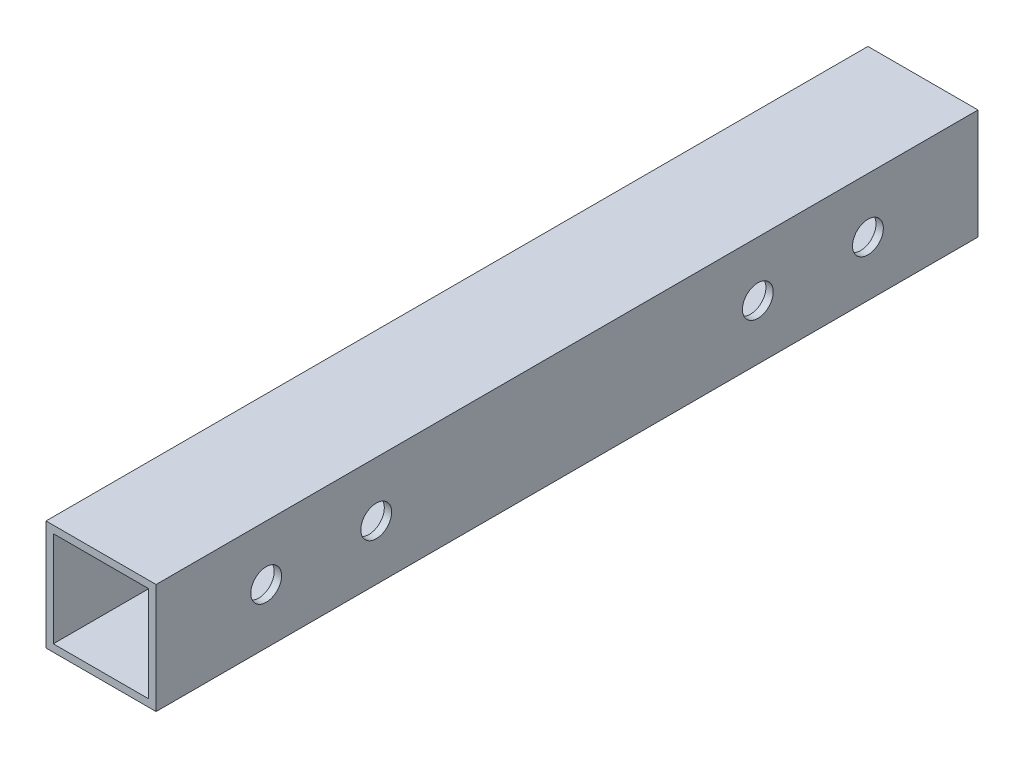
SolidWorks part; units mm, degrees
ref_plane "前视基准面" through (0, 0, 0) normal (0, 0, 1) x (1, 0, 0)
ref_plane "上视基准面" through (0, 0, 0) normal (0, 1, 0) x (1, 0, 0)
ref_plane "右视基准面" through (0, 0, 0) normal (1, 0, 0) x (0, 0, -1)
other "Configuration Table"
sketch "草图1" plane through (0, 0, 0) normal (0, 0, 1) x (1, 0, 0)
  line L1 (-7.5, 7.5) -> (7.5, 7.5)
  line L2 (-7.5, 7.5) -> (-7.5, -7.5)
  line L3 (-7.5, -7.5) -> (7.5, -7.5)
  line L4 (7.5, 7.5) -> (7.5, -7.5)
  line L5 (-7.5, 7.5) -> (7.5, -7.5) construction
  line L6 (-7.5, -7.5) -> (7.5, 7.5) construction
  line L7 (-6.5, 6.5) -> (6.5, 6.5)
  line L8 (-6.5, 6.5) -> (-6.5, -6.5)
  line L9 (-6.5, -6.5) -> (6.5, -6.5)
  line L10 (6.5, 6.5) -> (6.5, -6.5)
  line L11 (-6.5, 6.5) -> (6.5, -6.5) construction
  line L12 (-6.5, -6.5) -> (6.5, 6.5) construction
  point P0 (0, 0)
  point P5 (0, 0)
  dimension "D1" = 15
  dimension "D2" = 15
  dimension "D3" = 1
extrude "凸台-拉伸1" add sketch "草图1" along normal blind 112
sketch "草图3" plane through (7.5, 0, 0) normal (1, 0, 0) x (0, 0, -1)
  line L0 (-112, 0) -> (0, 0) construction
  line L1 (-112, -7.5) -> (-112, 7.5) construction
  line L2 (0, -7.5) -> (0, 7.5) construction
  line L3 (-56, 7.5) -> (-56, -7.5) construction
  line L4 (-112, 7.5) -> (0, 7.5) construction
  line L5 (-112, -7.5) -> (0, -7.5) construction
  circle A0 centre (-15, 0) radius 2.1
  circle A1 centre (-30, 0) radius 2.1
  circle A2 centre (-97, 0) radius 2.1
  circle A3 centre (-82, 0) radius 2.1
  dimension "D1" = 15
  dimension "D3" = 4.2
  dimension "D2" = 15
extrude "切除-拉伸1" cut sketch "草图3" against normal blind 55
